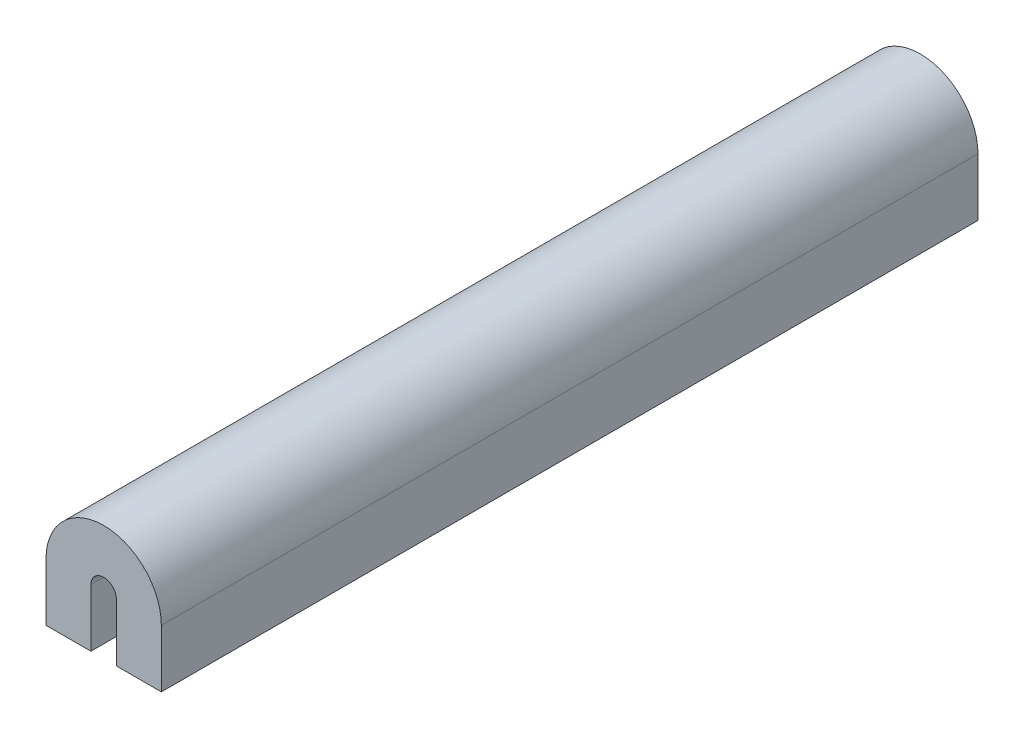
SolidWorks part; units mm, degrees
material "Rubber"
ref_plane "Front" through (0, 0, 0) normal (0, 0, 1) x (1, 0, 0)
ref_plane "Top" through (0, 0, 0) normal (0, 1, 0) x (1, 0, 0)
ref_plane "Right" through (0, 0, 0) normal (1, 0, 0) x (0, 0, -1)
sketch "Sketch1" plane through (0, 0, 0) normal (0, 0, 1) x (1, 0, 0)
  line L0 (0, 0) -> (0, -6.2164) construction
  line L1 (-1.5875, 0) -> (-1.5875, -7.1755)
  line L2 (1.5875, 0) -> (1.5875, -7.1755)
  line L4 (-7.1755, 0) -> (-7.1755, -7.1755)
  line L5 (-7.1755, -7.1755) -> (-1.5875, -7.1755)
  line L7 (7.1755, 0) -> (7.1755, -7.1755)
  line L8 (7.1755, -7.1755) -> (1.5875, -7.1755)
  line L9 (0, 0) -> (0, -7.1755) construction
  arc A0 (7.1755, 0) -> (-7.1755, 0) centre (0, 0) ccw
  arc A1 (1.5875, 0) -> (-1.5875, 0) centre (0, 0) ccw
  dimension "D2" = 5.588
  dimension "D1" = 1.5875
extrude "Boss-Extrude1" add sketch "Sketch1" along normal blind 101.6
